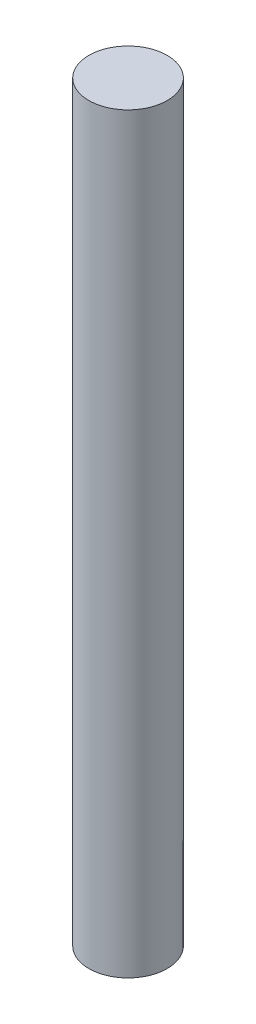
SolidWorks part; units mm, degrees
ref_plane "Front Plane" through (0, 0, 0) normal (0, 0, 1) x (1, 0, 0)
ref_plane "Top Plane" through (0, 0, 0) normal (0, 1, 0) x (1, 0, 0)
ref_plane "Right Plane" through (0, 0, 0) normal (1, 0, 0) x (0, 0, -1)
sketch "Sketch1" plane through (0, 0, 0) normal (0, 1, 0) x (1, 0, 0)
  circle A0 centre (0, 0) radius 15.875
  dimension "D1" = 31.75
extrude "Boss-Extrude1" add sketch "Sketch1" along normal blind 304.8
